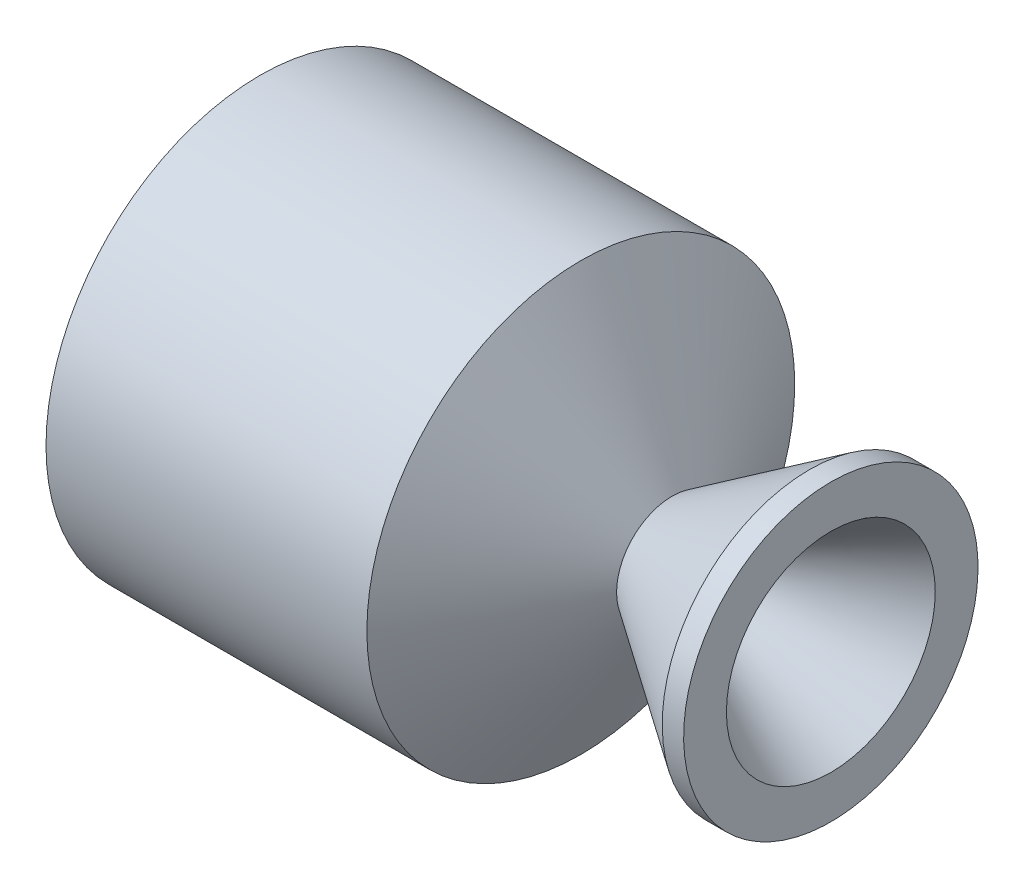
SolidWorks part; units mm, degrees
material "6061 Alloy"
ref_plane "Front Plane" through (0, 0, 0) normal (0, 0, 1) x (1, 0, 0)
ref_plane "Top Plane" through (0, 0, 0) normal (0, 1, 0) x (1, 0, 0)
ref_plane "Right Plane" through (0, 0, 0) normal (1, 0, 0) x (0, 0, -1)
sketch "Sketch1" plane through (0, 0, 0) normal (0, 0, 1) x (1, 0, 0)
  line L0 (0, 0) -> (0, 0.6) construction
  line L1 (0, 0.6) -> (7.4158, 4.8815)
  line L2 (7.4158, 4.8815) -> (7.4158, 0) construction
  line L3 (7.4158, 0) -> (0, 0) construction
  line L4 (7.4158, 4.8815) -> (7.4158, 6.8815)
  line L5 (7.4158, 6.8815) -> (6.4158, 6.8815)
  line L6 (6.4158, 6.8815) -> (0, 2.6)
  line L7 (0, 2.6) -> (-4.2724, 10)
  line L8 (-4.2724, 10) -> (-19.2724, 10)
  line L9 (-19.2724, 10) -> (-19.2724, 0.6)
  line L10 (0, 0.6) -> (-4.8497, 9)
  line L11 (-4.8497, 9) -> (-18.2724, 9)
  line L12 (-18.2724, 9) -> (-18.2724, 0.6)
  line L13 (-18.2724, 0.6) -> (-19.2724, 0.6)
  dimension "D1" = 0.6
  dimension "D2" = 7.4158
  dimension "D3" = 4.8815
  dimension "D4" = 2
  dimension "D5" = 1
  dimension "D6" = 2
  dimension "D7" = 60
  dimension "D8" = 10
  dimension "D9" = 15
  dimension "D10" = 1
  dimension "D11" = 1
revolve "Revolve1" add sketch "Sketch1" angle 360 about L3
equation "\"r_throat\"=0.6mm'min r"
equation "\"area_ratio\"= 66.19265'AR"
equation "\"r_exit\"= \"r_throat\" * sqr ( \"area_ratio\" )'max r"
equation "\"L\"= ( \"r_exit\" - \"r_throat\" ) / tan ( 30deg )'Nozzle Length (Diverg sect)"
equation "\"D1@Sketch1\"=\"r_throat\""
equation "\"D2@Sketch1\"=\"L\""
equation "\"D3@Sketch1\"=\"r_exit\""
equation "\"T1\"= 2mm'Primary thickness"
equation "\"T2\"= 1mm'Secondary thickness"
equation "\"D4@Sketch1\"=\"T1\""
equation "\"D5@Sketch1\"=\"T2\""
equation "\"D10@Sketch1\"=\"T2\""
equation "\"D11@Sketch1\"=\"T2\""
equation "\"D8@Sketch1\"=10"
